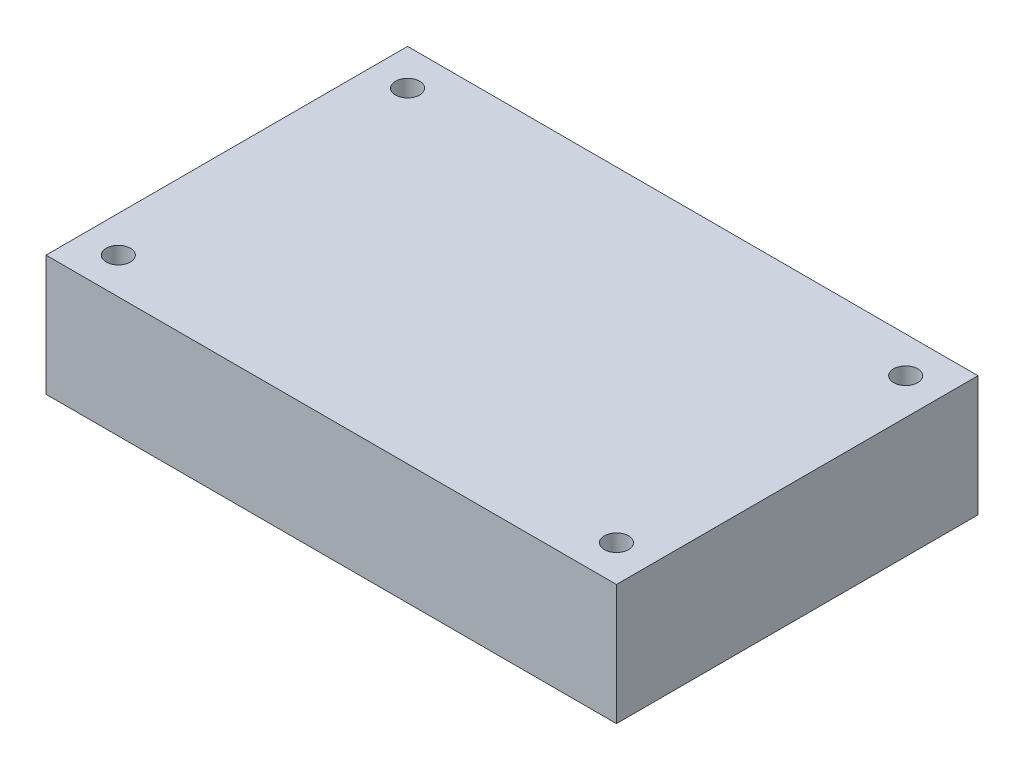
SolidWorks part; units mm, degrees
ref_plane "前视基准面" through (0, 0, 0) normal (0, 0, 1) x (1, 0, 0)
ref_plane "上视基准面" through (0, 0, 0) normal (0, 1, 0) x (1, 0, 0)
ref_plane "右视基准面" through (0, 0, 0) normal (1, 0, 0) x (0, 0, -1)
other "Configuration Table"
sketch "草图1" plane through (0, 0, 0) normal (0, 1, 0) x (1, 0, 0)
  line L1 (0, 0) -> (71, 0)
  line L2 (0, 0) -> (0, 45)
  line L3 (0, 45) -> (71, 45)
  line L4 (71, 0) -> (71, 45)
  circle A0 centre (4.5, 4.5) radius 1.5
  circle A1 centre (4.5, 40.5) radius 1.5
  circle A2 centre (66.5, 40.5) radius 1.5
  circle A3 centre (66.5, 4.5) radius 1.5
  point P15 (-29.98, 39.8801)
  dimension "D3" = 4.5
  dimension "D7" = 3
  dimension "D8" = 3
  dimension "D9" = 3
  dimension "D10" = 3
  dimension "D1" = 71
  dimension "D2" = 45
  dimension "D4" = 4.5
  dimension "D5" = 4.5
  dimension "D6" = 4.5
  dimension "D11" = 4.5
  dimension "D12" = 4.5
  dimension "D13" = 4.5
  dimension "D14" = 4.5
extrude "凸台-拉伸1" add sketch "草图1" along normal blind 15
